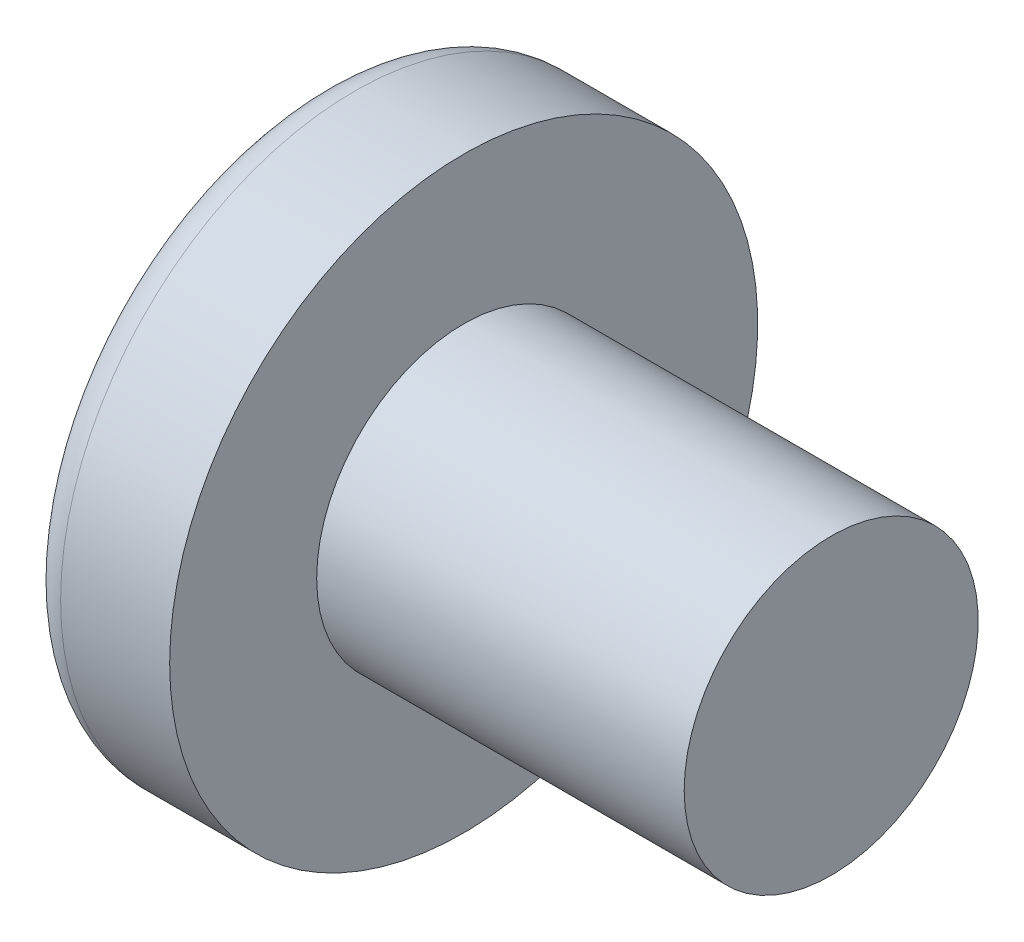
SolidWorks part; units mm, degrees
material "AISI 304"
ref_plane "Plane1" through (0, 0, 0) normal (0, 0, 1) x (1, 0, 0)
ref_plane "Plane2" through (0, 0, 0) normal (0, 1, 0) x (1, 0, 0)
ref_plane "Plane3" through (0, 0, 0) normal (1, 0, 0) x (0, 0, -1)
sketch "BodySke" plane through (0, 0, 0) normal (0, 0, 1) x (1, 0, 0)
  line L0 (3.1, 2) -> (3.1, 4)
  line L1 (3.8, 6.35) -> (3.8, -3.175) construction
  line L2 (-25.4, 0) -> (127, 0) construction
  line L3 (8.1, 0) -> (0, 0)
  line L4 (3.1, 2) -> (8.1, 2)
  line L5 (8.1, 2) -> (8.1, 0)
  line L6 (1.6164, 4) -> (3.1, 4)
  line L7 (3.1, -2) -> (8.1, -2) construction
  line L8 (3.1, 6.35) -> (3.1, -3.175) construction
  arc A0 (1.227, 3.8007) -> (0, 0) centre (6.5, 0) ccw
  arc A2 (1.227, 3.8007) -> (1.6164, 4) centre (1.6164, 3.52) cw
  dimension "Head_crown_rad" = 6.5
  dimension "Head_fillet_rad" = 0.48
  dimension "Diameter" = 4
  dimension "Length" = 5
  dimension "Head_ht" = 3.1
  dimension "Head_dia" = 8
  dimension "Advance" = 0.7
  dimension "Thread_nom" = 5
revolve "Base-Revolve" add sketch "BodySke" angle 360 about L2
cosmetic thread "ThreadCosmetic" [suppressed] parameters "Thread_length"=4.3, "Thread_minor"=3.22
sketch "Sketch3" plane through (0, 0, 0) normal (1, 0, 0) x (0, 0, -1)
  line L0 (0.465, -2.2) -> (-0.465, -2.2)
  line L1 (0.465, -2.2) -> (0.465, 2.2)
  line L2 (-0.465, 2.2) -> (0.465, 2.2)
  line L3 (-0.465, 2.2) -> (-0.465, -2.2)
  dimension "Cross_dia" = 4.4
  dimension "D1" = 2.2
  dimension "Cross_width" = 0.93
  dimension "D2" = 0.465
ref_plane "Plane4" through (2.45, 0, 0) normal (1, 0, 0) x (0, 0, -1)
sketch "Sketch4" plane through (2.45, 0, 0) normal (1, 0, 0) x (0, 0, -1)
  line L0 (0.2325, -0.2325) -> (-0.2325, -0.2325)
  line L1 (0.2325, -0.2325) -> (0.2325, 0.2325)
  line L2 (-0.2325, 0.2325) -> (0.2325, 0.2325)
  line L3 (-0.2325, 0.2325) -> (-0.2325, -0.2325)
  dimension "D2" = 0.465
  dimension "D1" = 0.465
  dimension "D3" = 0.2325
  dimension "D4" = 0.2325
loft "Cut-Loft1" cut profiles "Sketch3", "Sketch4"
pattern_circular "CirPattern1" count 2 every 90 about axis through (0, 0, 0) along (1, 0, 0) of "Cut-Loft1"
sketch "ThdSchSke" plane through (0, 0, 0) normal (0, 0, 1) x (1, 0, 0)
  line L0 (3.8, -1.61) -> (3.5269, -2)
  line L1 (3.8, -1.61) -> (4.0731, -2)
  line L2 (4.0731, -2) -> (4.0731, -2.5)
  line L3 (-3.175, 0) -> (5.1513, 0) construction
  line L5 (4.0731, -2.5) -> (3.5269, -2.5)
  line L6 (3.5269, -2.5) -> (3.5269, -2)
  dimension "Diameter" = 4
  dimension "SideAngle" = 55
  dimension "VeeAngle" = 70
  dimension "Thread_minor" = 3.22
  dimension "Overcut" = 5
  dimension "Start" = 3.8
revolve "ThreadSchematic" [suppressed] cut sketch "ThdSchSke" angle 360 about L3
pattern_linear "ThdSchPat" [suppressed]
equation "\"D1@Sketch3\" = \"Cross_dia@Sketch3\" / 2"
equation "\"D2@Sketch3\" = \"Cross_width@Sketch3\" / 2"
equation "\"D1@Sketch4\" = \"Cross_width@Sketch3\" *.5"
equation "\"D2@Sketch4\" = \"D1@Sketch4\""
equation "\"D3@Sketch4\" = \"D1@Sketch4\" / 2"
equation "\"D4@Sketch4\" = \"D2@Sketch4\" / 2"
equation "\"Thread_length@ThreadCosmetic\" = ((sgn( (\"Length@BodySke\" - \"Advance@BodySke\" ) - \"Thread_nom@BodySke\" )-1)*( (\"Length@BodySke\" - \"Advance@BodySke\" ) - \"Thread_nom@BodySke\" ))/-2+ \"Thread_nom@BodySke\""
equation "\"Thread_minor@ThdSchSke\" = \"Thread_minor@ThreadCosmetic\""
equation "\"Diameter@ThdSchSke\" = \"Diameter@BodySke\""
equation "\"Overcut@ThdSchSke\" = \"Diameter@BodySke\" * 1.25"
equation "\"Start@ThdSchSke\" = \"Head_ht@BodySke\" + \"Length@BodySke\" - \"Thread_length@ThreadCosmetic\"  '---Non-countersunk---"
equation "\"Num_threads@ThdSchPat\" = int( \"Thread_length@ThreadCosmetic\" / \"Advance@BodySke\" + 0.999 )  + 1"
equation "\"Advance@ThdSchPat\" = \"Thread_length@ThreadCosmetic\" /  (\"Num_threads@ThdSchPat\" - 1) 'relax it"
